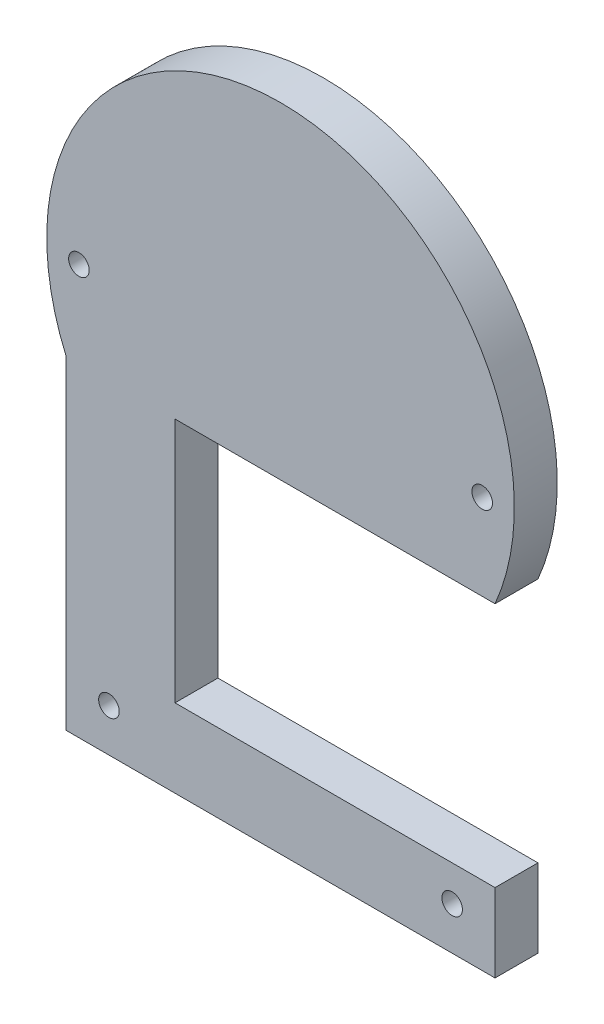
SolidWorks part; units mm, degrees
ref_plane "Front Plane" through (0, 0, 0) normal (0, 0, 1) x (1, 0, 0)
ref_plane "Top Plane" through (0, 0, 0) normal (0, 1, 0) x (1, 0, 0)
ref_plane "Right Plane" through (0, 0, 0) normal (1, 0, 0) x (0, 0, -1)
sketch "Sketch1" plane through (0, 0, 0) normal (0, 0, 1) x (-1, 0, 0)
  line L0 (-50, 21.6852) -> (-50, 97.2352)
  line L1 (-50, 97.2352) -> (50, 97.2352)
  line L2 (50, 97.2352) -> (50, 21.6852)
  arc A0 (-50, 21.6852) -> (50, 21.6852) centre (0, 0) ccw
extrude "Boss-Extrude1" add sketch "Sketch1" along normal blind 10
sketch "Sketch3" plane through (0, 0, 0) normal (0, 0, -1) x (-1, 0, 0)
  line L0 (50, -97.2352) -> (-50, -97.2352) construction
  line L1 (-50, -97.2352) -> (-50, -21.6852) construction
  line L2 (50, -21.6852) -> (50, -97.2352) construction
  point P0 (40, -87.2352)
  point P1 (-40, -87.2352)
  point P2 (-47, -1.6852)
  point P3 (47, -1.6852)
  dimension "D1" = 10
  dimension "D2" = 10
  dimension "D3" = 10
  dimension "D4" = 10
  dimension "D5" = 3
  dimension "D6" = 20
  dimension "D7" = 20
  dimension "D8" = 3
hole_wizard "CSK for M4 Flat Head Machine Screw1" positions "3DSketch1" profile "Sketch5" countersink size "M4" standard "ANSI Metric" end condition up to next
sketch3d "3DSketch1"
  point P0 (47, -1.6852, 0)
  point P3 (-47, -1.6852, 0)
  point P6 (-40, -87.2352, 0)
  point P9 (40, -87.2352, 0)
sketch "Sketch5" plane through (47, -1.6852, 0) normal (1, 0, 0) x (0, 1, 0)
  line L0 (0, 0) -> (0, 10)
  line L1 (0, 10) -> (2.4, 10)
  line L2 (2.4, 10) -> (2.4, 2.3)
  line L3 (2.4, 2.3) -> (4.7, 0)
  line L5 (4.7, 0) -> (0, 0)
  line L6 (-2.4, 2.3) -> (-4.7, 0) construction
  line L11 (0, -6.35) -> (0, 107.95) construction
  dimension "Thru Hole Dia." = 4.8
  dimension "Thru Hole Depth" = 10
  dimension "Near C'Sink Dia." = 9.4
  dimension "Near C'Sink Angle" = 90
sketch "Sketch6" plane through (0, 0, 10) normal (0, 0, 1) x (1, 0, 0)
  line L1 (50, -21.6852) -> (-24.6, -21.6852)
  line L2 (50, -21.6852) -> (50, -78.9852)
  line L3 (50, -78.9852) -> (-24.6, -78.9852)
  line L4 (-24.6, -21.6852) -> (-24.6, -78.9852)
  dimension "D1" = 57.3
  dimension "D2" = 74.6
extrude "Cut-Extrude1" cut sketch "Sketch6" against normal blind 15
